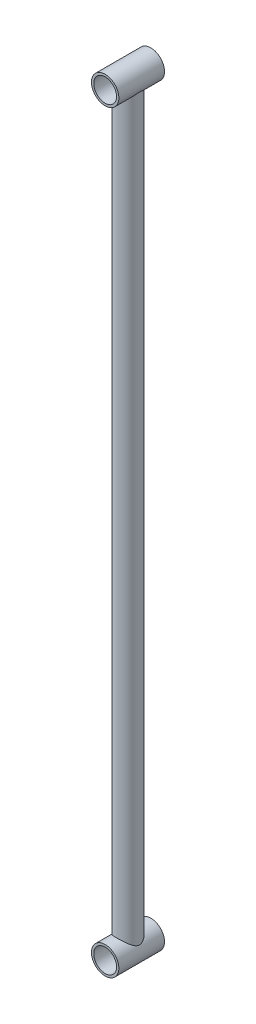
SolidWorks part; units mm, degrees
material "1023 Carbon Steel Sheet (SS)"
ref_plane "Front Plane" through (0, 0, 0) normal (0, 0, 1) x (1, 0, 0)
ref_plane "Top Plane" through (0, 0, 0) normal (0, 1, 0) x (1, 0, 0)
ref_plane "Right Plane" through (0, 0, 0) normal (1, 0, 0) x (0, 0, -1)
sketch "Sketch3" plane through (0, 0, 0) normal (0, 1, 0) x (1, 0, 0)
  circle A0 centre (0, 0) radius 3.175
  dimension "D1" = 6.35
extrude "Boss-Extrude1" add sketch "Sketch3" along normal mid plane 209.55
sketch "Sketch4" plane through (0, 0, 0) normal (0, 0, 1) x (1, 0, 0)
  line L0 (3.175, 104.775) -> (-3.175, 104.775) construction
  circle A1 centre (0, 104.775) radius 3.81
  dimension "D1" = 7.62
extrude "Boss-Extrude2" add sketch "Sketch4" along normal mid plane 12.7
sketch "Sketch5" plane through (0, 0, 6.35) normal (0, 0, 1) x (1, 0, 0)
  circle A0 centre (0, 104.775) radius 3.175
  circle A1 centre (0, 104.775) radius 3.81 construction
  dimension "D1" = 6.35
extrude "Cut-Extrude1" cut sketch "Sketch5" against normal up to surface (12.7 mm away) up to face at (3.81, 104.775, -6.35)
mirror "Mirror1" about plane through (0, 0, 0) normal (0, 1, 0) of "Cut-Extrude1", "Boss-Extrude2"
